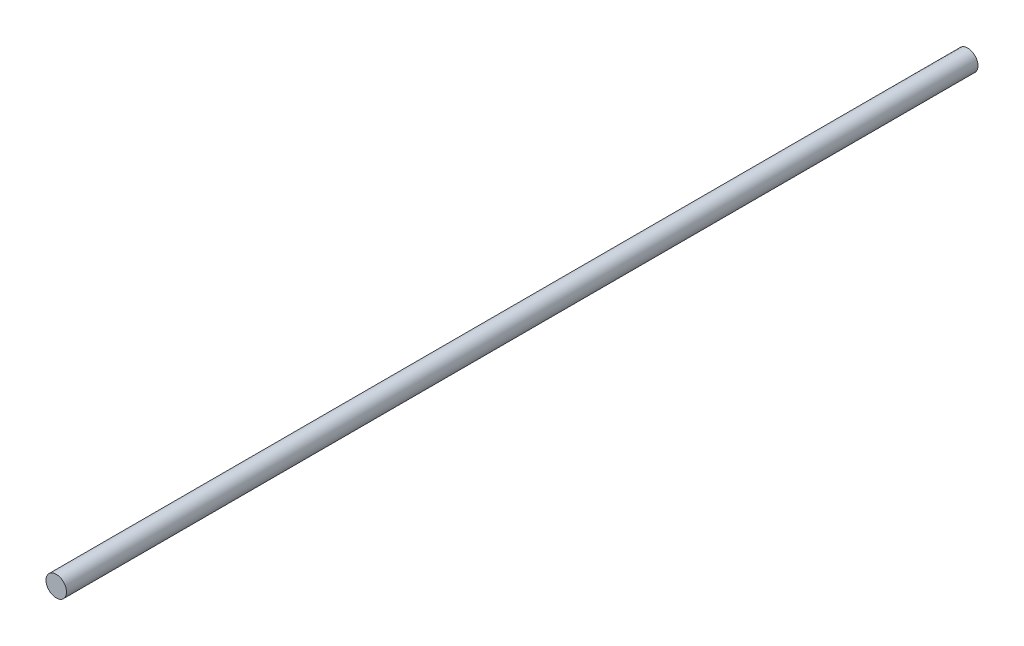
SolidWorks part; units mm, degrees
ref_plane "Alzado" through (0, 0, 0) normal (0, 0, 1) x (1, 0, 0)
ref_plane "Planta" through (0, 0, 0) normal (0, 1, 0) x (1, 0, 0)
ref_plane "Vista lateral" through (0, 0, 0) normal (1, 0, 0) x (0, 0, -1)
sketch "Croquis1" plane through (0, 0, 0) normal (0, 0, 1) x (1, 0, 0)
  circle A0 centre (0, 0) radius 4.5
  dimension "D1" = 9
extrude "Saliente-Extruir1" add sketch "Croquis1" along normal blind 400
